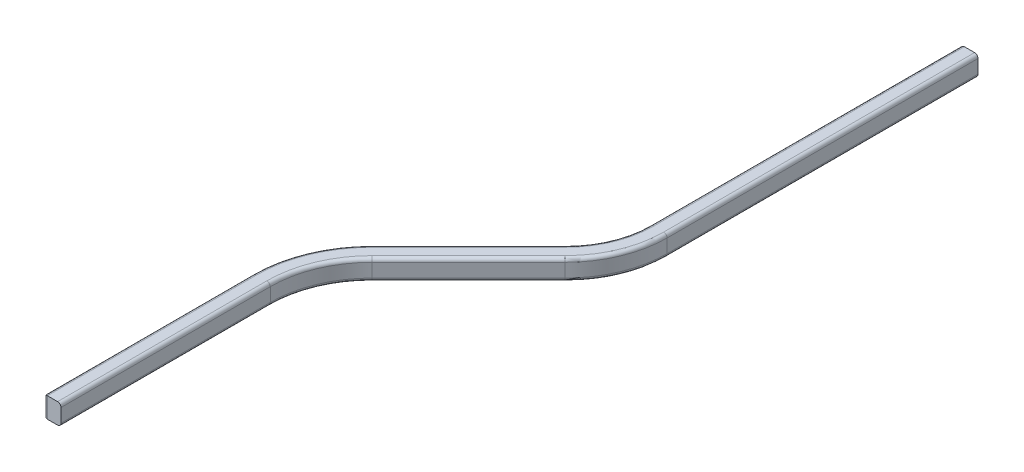
SolidWorks part; units mm, degrees
ref_plane "Plano frontal" through (0, 0, 0) normal (0, 0, 1) x (1, 0, 0)
ref_plane "Plano superior" through (0, 0, 0) normal (0, 1, 0) x (1, 0, 0)
ref_plane "Plano direito" through (0, 0, 0) normal (1, 0, 0) x (0, 0, -1)
sketch "Esboço2" plane through (0, 0, 0) normal (0, 1, 0) x (1, 0, 0)
  line L0 (-11.375, -102.8285) -> (-11.375, -41.2126)
  line L2 (-1.1237, -16.4638) -> (27.3027, 11.9626)
  line L4 (34.625, 29.6402) -> (34.625, 121.1715)
  line L6 (-6.375, -102.8285) -> (-11.375, -102.8285)
  line L8 (39.625, 29.6402) -> (39.625, 121.1715)
  line L11 (2.4118, -19.9994) -> (30.8382, 8.427)
  line L12 (-6.375, -102.8285) -> (-6.375, -41.2126)
  line L21 (34.625, 121.1715) -> (39.625, 121.1715)
  arc A0 (2.4118, -19.9994) -> (-6.375, -41.2126) centre (23.625, -41.2126) ccw
  arc A2 (39.625, 29.6402) -> (30.8382, 8.427) centre (9.625, 29.6402) cw
  arc A4 (-1.1237, -16.4638) -> (-11.375, -41.2126) centre (23.625, -41.2126) ccw
  arc A5 (34.625, 29.6402) -> (27.3027, 11.9626) centre (9.625, 29.6402) cw
  point P16 (-6.375, -28.7862)
  point P21 (39.625, 17.2138)
  dimension "D3" = 30
  dimension "D1" = 103.9577
  dimension "D2" = 65.0538
  dimension "D4" = 61.6159
  dimension "D5" = 5
extrude "Ressalto-extrusão1" add sketch "Esboço2" along normal blind 6
fillet "Filete1" radius 1 22 edges at (34.625, 3, -121.1715) (-11.375, 3, 102.8285) (34.625, 0, -75.4059) (32.722, 0, -20.0732) (13.0895, 0, 2.2506) (-8.7108, 0, 27.8187) (-11.375, 0, 72.0205) (-6.375, 0, 72.0205) (-4.0914, 0, 29.7321) (16.625, 0, 5.7862) (37.3414, 0, -18.1597) (39.625, 0, -75.4059) (39.625, 6, -75.4059) (37.3414, 6, -18.1597) (16.625, 6, 5.7862) (-4.0914, 6, 29.7321) (-6.375, 6, 72.0205) (-11.375, 6, 72.0205) (-8.7108, 6, 27.8187) (13.0895, 6, 2.2506) (32.722, 6, -20.0732) (34.625, 6, -75.4059)
